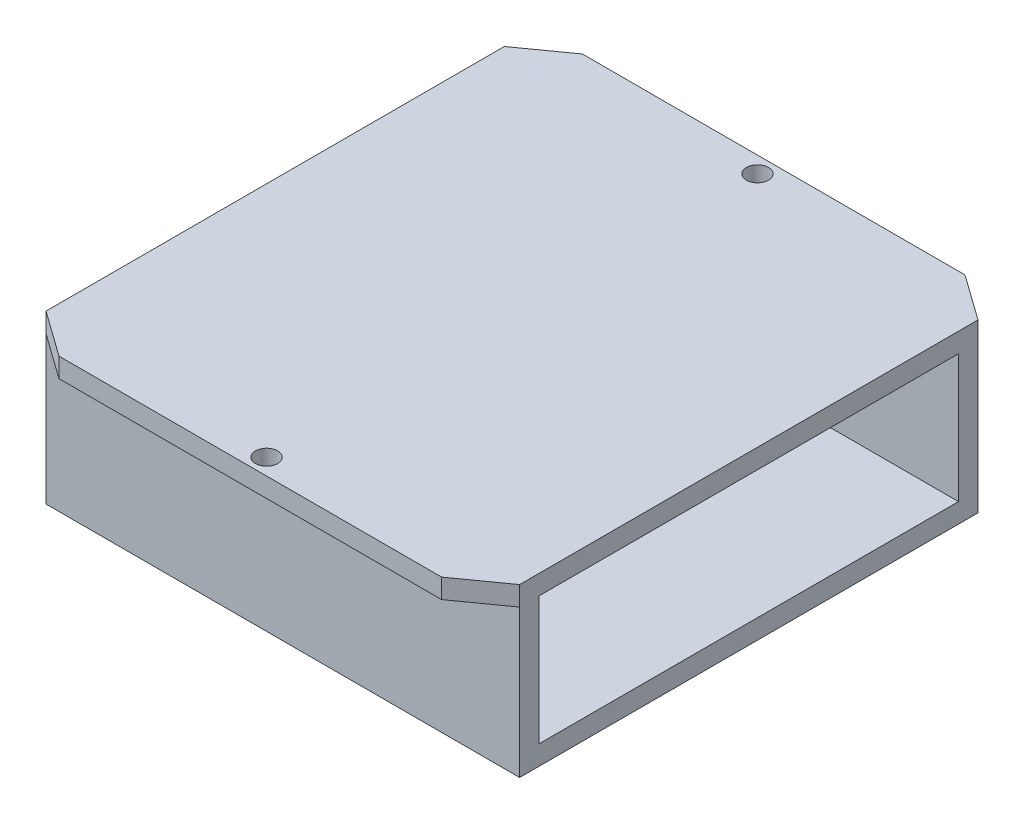
SolidWorks part; units mm, degrees
ref_plane "Front Plane" through (0, 0, 0) normal (0, 0, 1) x (1, 0, 0)
ref_plane "Top Plane" through (0, 0, 0) normal (0, 1, 0) x (1, 0, 0)
ref_plane "Right Plane" through (0, 0, 0) normal (1, 0, 0) x (0, 0, -1)
sketch "Sketch2" plane through (0, 0, 0) normal (1, 0, 0) x (0, 0, -1)
  line L0 (-3, 22.7) -> (67.5, 22.7)
  line L1 (0, 0) -> (64.5, 0)
  line L2 (0, 0) -> (0, 19.7)
  line L3 (0, 19.7) -> (64.5, 19.7)
  line L4 (64.5, 0) -> (64.5, 19.7)
  line L5 (67.5, -3) -> (67.5, 22.7)
  line L6 (-3, -3) -> (67.5, -3)
  line L7 (-3, -3) -> (-3, 22.7)
  dimension "D1" = 64.5
  dimension "D2" = 19.7
  dimension "D3" = 3
extrude "Boss-Extrude1" add sketch "Sketch2" along normal blind 69.85
sketch "Sketch3" plane through (0, 0, 0) normal (-1, 0, 0) x (0, 0, 1)
  line L4 (3, -3) -> (3, 22.7)
  line L5 (3, 22.7) -> (-67.5, 22.7)
  line L6 (-67.5, 22.7) -> (-67.5, -3)
  line L7 (-67.5, -3) -> (3, -3)
  line L8 (3, -3) -> (3, 22.7)
  line L9 (3, 22.7) -> (-67.5, 22.7)
  line L10 (-67.5, 22.7) -> (-67.5, -3)
  line L11 (-67.5, -3) -> (3, -3)
  dimension "D1" = 0
extrude "Boss-Extrude2" add sketch "Sketch3" along normal blind 3
sketch "Sketch4" plane through (0, 22.7, 0) normal (0, 1, 0) x (1, 0, 0)
  line L4 (69.85, 67.5) -> (62.85, 72.5)
  line L7 (62.85, 72.5) -> (4, 72.5)
  line L8 (4, 72.5) -> (-3, 67.5)
  line L9 (-3, 67.5) -> (69.85, 67.5)
  line L10 (62.85, 72.5) -> (62.85, 67.5) construction
  line L15 (33.425, 72.5) -> (33.425, 67.5) construction
  line L16 (-3, 32.25) -> (69.85, 32.25) construction
  line L17 (-3, -3) -> (-3, 67.5) construction
  line L18 (69.85, 67.5) -> (69.85, -3) construction
  line L19 (33.425, -8) -> (33.425, -3) construction
  line L20 (62.85, -8) -> (62.85, -3) construction
  line L21 (-3, -3) -> (69.85, -3)
  line L22 (4, -8) -> (-3, -3)
  line L23 (62.85, -8) -> (4, -8)
  line L24 (69.85, -3) -> (62.85, -8)
  circle A2 centre (33.425, 70) radius 1.7
  circle A3 centre (33.425, -5.5) radius 1.7
  dimension "D3" = 3.4
  dimension "D1" = 5
  dimension "D2" = 7
extrude "Boss-Extrude3" add sketch "Sketch4" against normal blind 3
